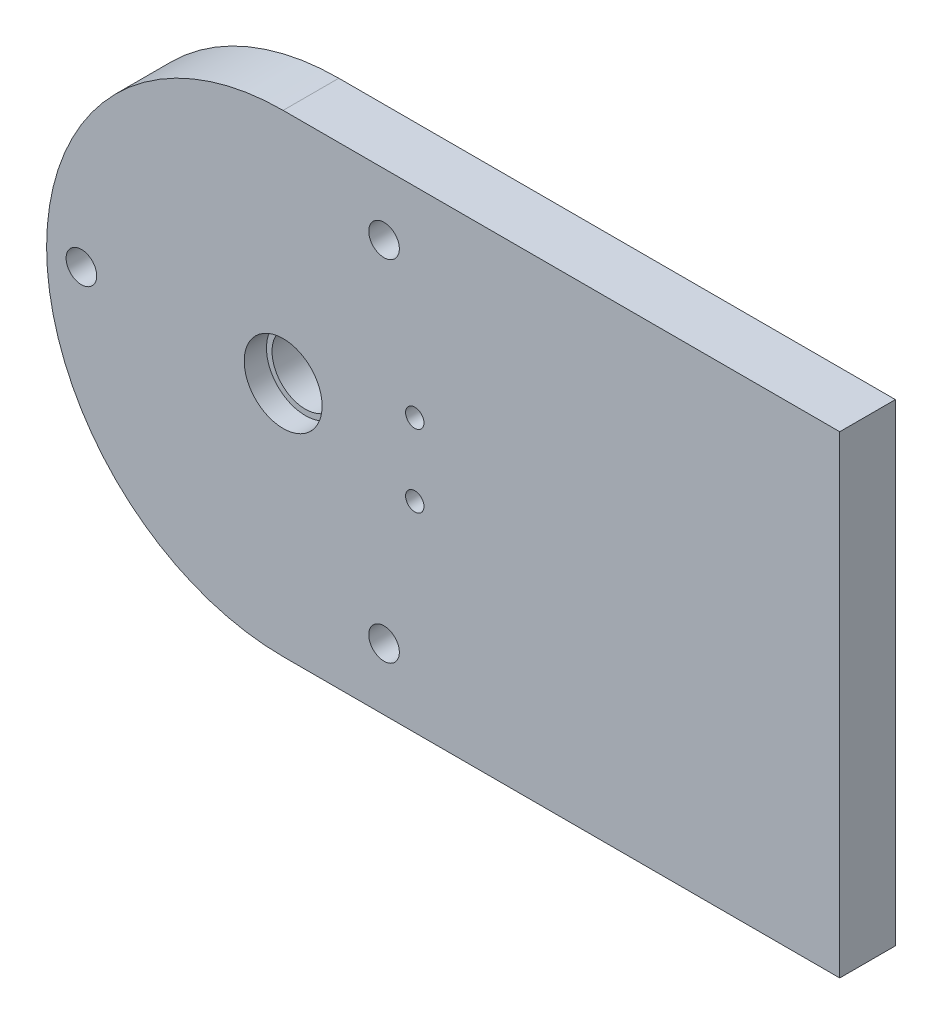
SolidWorks part; units mm, degrees
ref_plane "前视基准面" through (0, 0, 0) normal (0, 0, 1) x (1, 0, 0)
ref_plane "上视基准面" through (0, 0, 0) normal (0, 1, 0) x (1, 0, 0)
ref_plane "右视基准面" through (0, 0, 0) normal (1, 0, 0) x (0, 0, -1)
sketch "草图1" plane through (0, 0, 0) normal (0, 0, 1) x (1, 0, 0)
  line L0 (0, 85) -> (200, 85)
  line L1 (200, 85) -> (200, -85)
  line L2 (200, -85) -> (0, -85)
  arc A1 (0, 85) -> (0, -85) centre (0, 0) ccw
  dimension "D1" = 85
  dimension "D2" = 200
extrude "凸台-拉伸1" add sketch "草图1" along normal blind 20
sketch "草图2" plane through (0, 0, 20) normal (0, 0, 1) x (1, 0, 0)
  circle A0 centre (0, 0) radius 14
extrude "切除-拉伸1" cut sketch "草图2" against normal blind 8
sketch "草图3" plane through (0, 0, 12) normal (0, 0, 1) x (1, 0, 0)
  circle A0 centre (0, 0) radius 12
extrude "切除-拉伸2" cut sketch "草图3" against normal through all
sketch "草图4" plane through (0, 0, 20) normal (0, 0, 1) x (1, 0, 0)
  line L0 (-72.5, 0) -> (0, 0) construction
  line L2 (200, 85) -> (0, 85) construction
  circle A0 centre (0, 0) radius 72.5 construction
  circle A1 centre (-72.5, 0) radius 5.5
  circle A2 centre (36.25, 62.7868) radius 5.5
  circle A3 centre (36.25, -62.7868) radius 5.5
  point P14 (0, 0)
  dimension "D1" = 3
extrude "切除-拉伸3" cut sketch "草图4" against normal through all
sketch "草图6" plane through (0, 0, 20) normal (0, 0, 1) x (1, 0, 0)
  line L0 (47.3, 85) -> (47.3, -85) construction
  line L1 (200, 85) -> (0, 85) construction
  line L2 (0, -85) -> (200, -85) construction
  line L3 (200, -85) -> (200, 85) construction
  circle A0 centre (47.3, 13) radius 3.3
  circle A1 centre (47.3, -13) radius 3.3
  point P12 (47.3, 0)
  dimension "D3" = 47.3
  dimension "D1" = 13
  dimension "D2" = 26
extrude "切除-拉伸4" cut sketch "草图6" against normal through all
